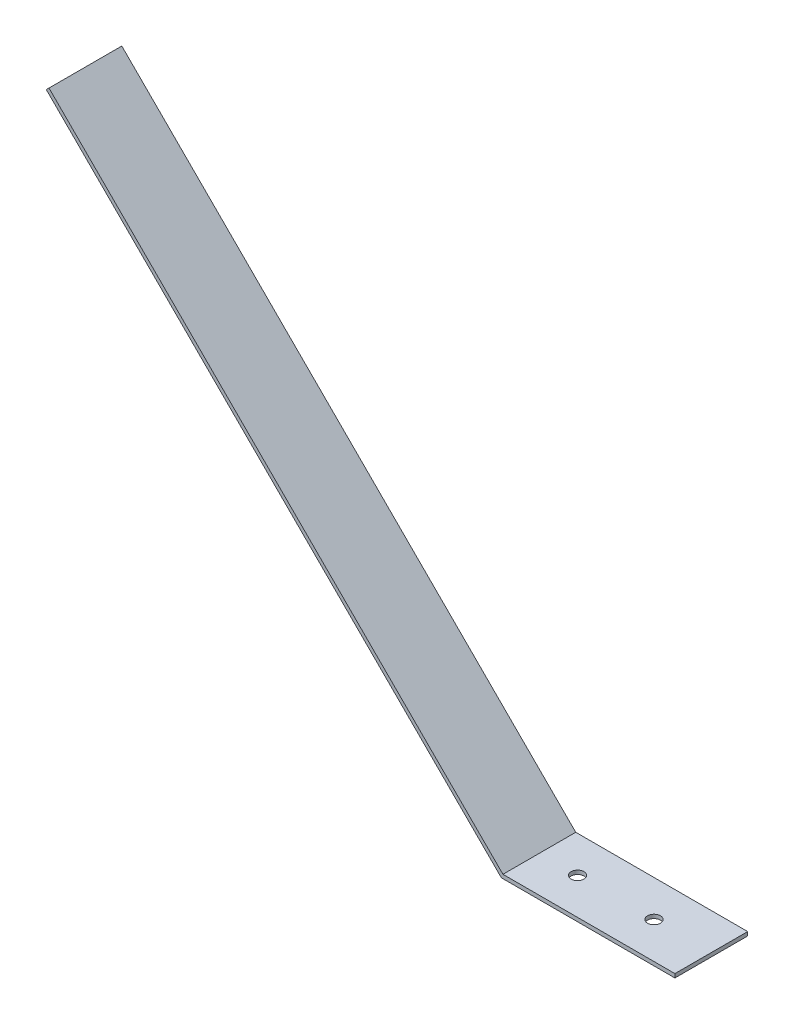
SolidWorks part; units mm, degrees
ref_plane "Alzado" through (0, 0, 0) normal (0, 0, 1) x (1, 0, 0)
ref_plane "Planta" through (0, 0, 0) normal (0, 1, 0) x (1, 0, 0)
ref_plane "Vista lateral" through (0, 0, 0) normal (1, 0, 0) x (0, 0, -1)
sketch "Croquis1" plane through (0, 0, 0) normal (0, 0, 1) x (1, 0, 0)
  line L0 (0, 0) -> (-90, 0)
  line L1 (-90, 0) -> (-327.5879, 237.5879)
  line L2 (0, -2) -> (-90.8284, -2)
  line L3 (-90.8284, -2) -> (-329.0021, 236.1737)
  line L4 (-329.0021, 236.1737) -> (-327.5879, 237.5879)
  line L5 (0, -2) -> (0, 0)
  dimension "D1" = 135
  dimension "D3" = 90
  dimension "D4" = 336
  dimension "D2" = 2
extrude "Saliente-Extruir1" add sketch "Croquis1" along normal mid plane 38.1
hole_wizard "Taladro de margen para 1/41" positions "Croquis3D1" profile "Croquis3" hole size "1/4" standard "Ansi Inch" end condition through all
sketch3d "Croquis3D1"
  line L0 (0, 0, 19.05) -> (0, 0, -19.05) construction
  point P0 (-70, 0, 0)
  point P2 (-30, 0, 0)
  point P8 (0, 0, 0)
  point P9 (0, 0, 0)
  dimension "D1" = 40
  dimension "D2" = 30
sketch "Croquis3" plane through (-70, 0, 0) normal (1, 0, 0) x (0, 0, 1)
  line L0 (0, 0) -> (0, 2)
  line L1 (0, 2) -> (3.3782, 2)
  line L2 (3.3782, 2) -> (3.3782, 0)
  line L5 (3.3782, 0) -> (0, 0)
  line L11 (0, -6.35) -> (0, 107.95) construction
  dimension "Diámetro de taladro hasta el siguiente" = 6.7564
  dimension "Profundidad de taladro hasta el siguiente" = 2
